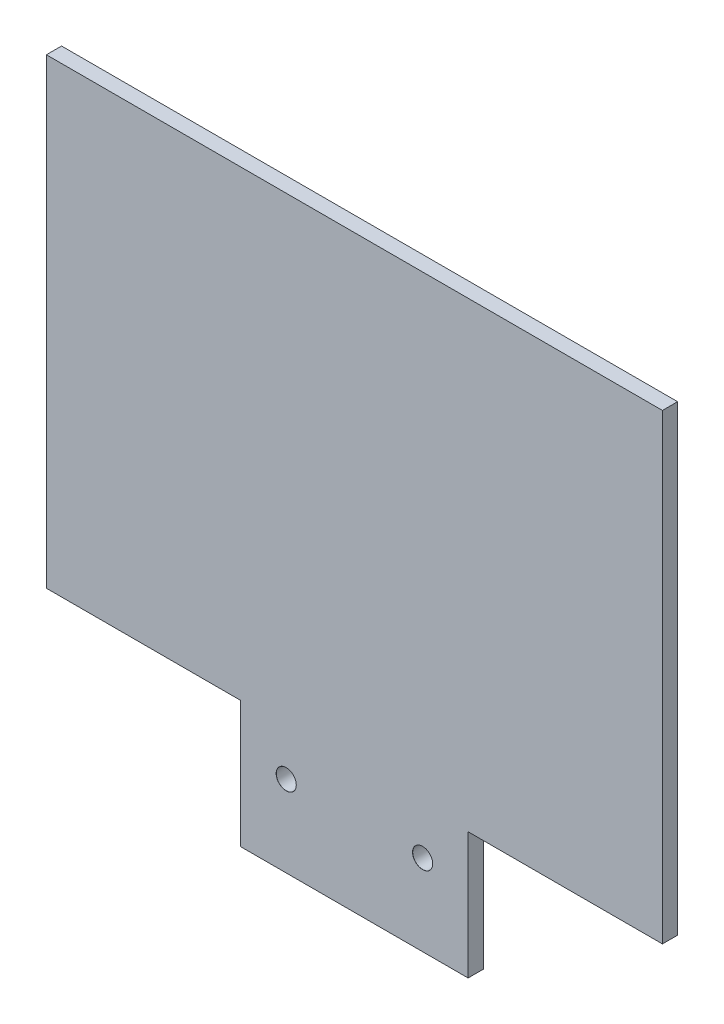
SolidWorks part; units mm, degrees
ref_plane "Front Plane" through (0, 0, 0) normal (0, 0, 1) x (1, 0, 0)
ref_plane "Top Plane" through (0, 0, 0) normal (0, 1, 0) x (1, 0, 0)
ref_plane "Right Plane" through (0, 0, 0) normal (1, 0, 0) x (0, 0, -1)
sketch "Sketch1" plane through (0, 0, 0) normal (0, 0, 1) x (1, 0, 0)
  line L1 (-37.5, -20.889) -> (37.5, -20.889)
  line L2 (-37.5, -20.889) -> (-37.5, 20.889)
  line L3 (-37.5, 20.889) -> (-22.5, 20.889) construction
  line L4 (37.5, -20.889) -> (37.5, 20.889)
  line L5 (-37.5, -20.889) -> (37.5, 20.889) construction
  line L6 (-37.5, 20.889) -> (37.5, -20.889) construction
  line L7 (-37.5, 20.889) -> (-22.5, 20.889) construction
  line L8 (-37.5, 20.889) -> (-37.5, 5.889) construction
  line L9 (-37.5, 5.889) -> (-22.5, 5.889) construction
  line L10 (-22.5, 20.889) -> (-22.5, 5.889) construction
  line L11 (37.5, 20.889) -> (22.5, 20.889) construction
  line L12 (37.5, 20.889) -> (37.5, 5.889)
  line L13 (37.5, 5.889) -> (22.5, 5.889) construction
  line L14 (22.5, 20.889) -> (22.5, 5.889) construction
  line L15 (-37.5, 20.889) -> (-22.5, 20.889) construction
  line L23 (0, 0) -> (0, 97.089) construction
  line L24 (-101.6, 173.289) -> (101.6, 173.289)
  line L25 (22.5, 20.889) -> (37.5, 20.889) construction
  line L26 (37.5, 20.889) -> (101.6, 20.889)
  line L27 (-101.6, 173.289) -> (-101.6, 20.889)
  line L29 (101.6, 173.289) -> (101.6, 20.889)
  line L30 (-101.6, 173.289) -> (101.6, 20.889) construction
  line L31 (-101.6, 20.889) -> (101.6, 173.289) construction
  line L32 (-37.5, 20.889) -> (-101.6, 20.889)
  point P0 (0, 0)
  point P12 (0, 97.089)
  dimension "D1" = 15
  dimension "D2" = 41.778
  dimension "D3" = 75
  dimension "D4" = 152.4
  dimension "D5" = 203.2
extrude "Boss-Extrude2" add sketch "Sketch1" along normal blind 5 contours L32 L2 L1 L4 L26 L29 L24 L27
hole_wizard "M6 Clearance Hole2" positions "Sketch4" profile "Sketch5" hole size "M6" standard "ANSI Metric" end condition through all
sketch "Sketch4" plane through (0, 0, 5) normal (0, 0, 1) x (1, 0, 0)
  point P0 (-22.5, 5.889)
  point P3 (22.5, 5.889)
sketch "Sketch5" plane through (-22.5, 5.889, 5) normal (1, 0, 0) x (0, -1, 0)
  line L0 (0, 0) -> (0, 5)
  line L1 (0, 5) -> (3.3, 5)
  line L2 (3.3, 5) -> (3.3, 0.025)
  line L3 (3.3, 0.025) -> (3.325, 0)
  line L5 (3.325, 0) -> (0, 0)
  line L6 (-3.3, 0.025) -> (-3.325, 0) construction
  line L11 (0, -6.35) -> (0, 107.95) construction
  dimension "Thru Hole Dia." = 6.6
  dimension "Thru Hole Depth" = 5
  dimension "Near C'Sink Dia." = 6.65
  dimension "Near C'Sink Angle" = 90
